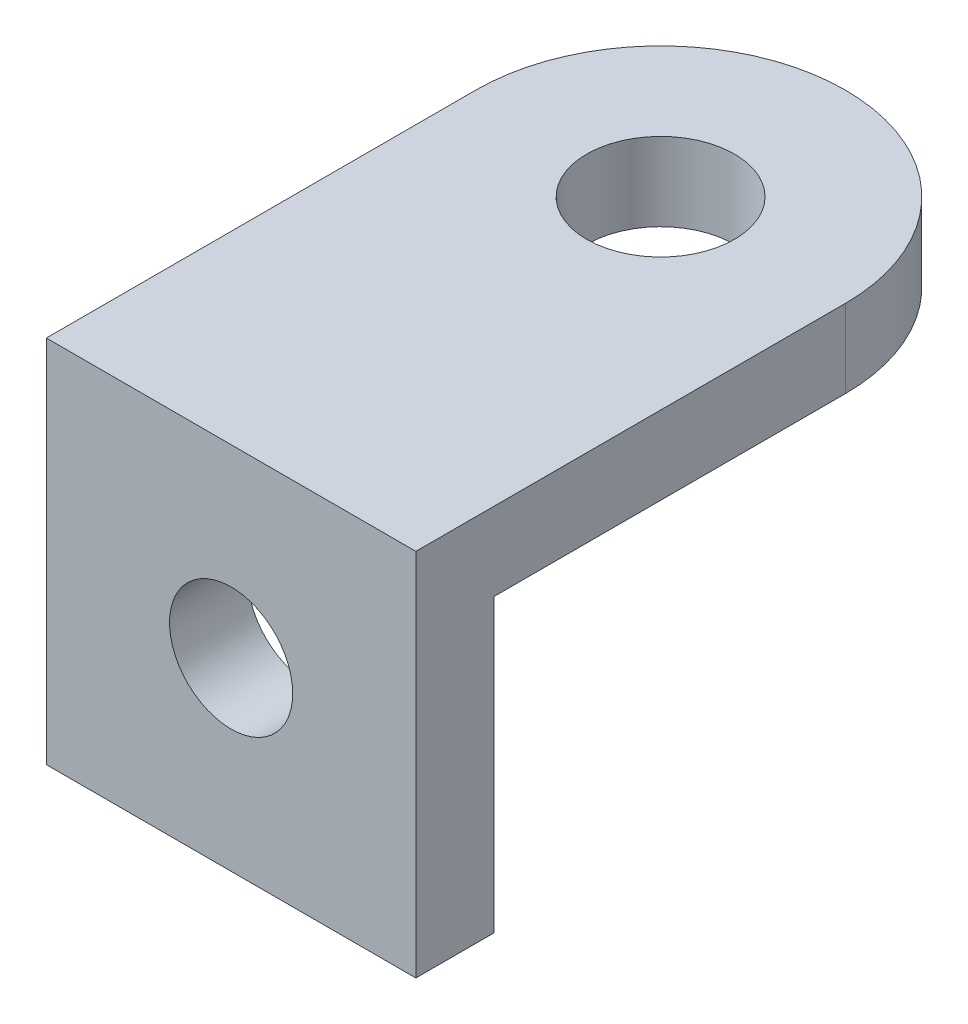
SolidWorks part; units mm, degrees
ref_plane "Front Plane" through (0, 0, 0) normal (0, 0, 1) x (1, 0, 0)
ref_plane "Top Plane" through (0, 0, 0) normal (0, 1, 0) x (1, 0, 0)
ref_plane "Right Plane" through (0, 0, 0) normal (1, 0, 0) x (0, 0, -1)
sketch "Sketch1" plane through (0, 0, 0) normal (0, 0, 1) x (1, 0, 0)
  line L1 (-7.5, 0) -> (7.5, 0)
  line L2 (-7.5, 0) -> (-7.5, -15)
  line L3 (-7.5, -15) -> (7.5, -15)
  line L4 (7.5, 0) -> (7.5, -15)
  line L5 (-7.5, 0) -> (7.5, -15) construction
  line L6 (-7.5, -15) -> (7.5, 0) construction
  circle A0 centre (0, -7.5) radius 2.5
  point P0 (0, -7.5)
  dimension "D3" = 5
  dimension "D1" = 15
  dimension "D2" = 15
extrude "Boss-Extrude1" add sketch "Sketch1" along normal blind 3.175
sketch "Sketch2" plane through (0, 0, 0) normal (0, 1, 0) x (1, 0, 0)
  line L6 (-7.5, 14.26) -> (-7.5, 0)
  line L7 (-7.5, 0) -> (7.5, 0)
  line L8 (7.5, 0) -> (7.5, 14.26)
  line L10 (0, 14.26) -> (0, 0) construction
  circle A0 centre (0, 14.26) radius 3
  arc A3 (7.5, 14.26) -> (-7.5, 14.26) centre (0, 14.26) ccw
  point P1 (-7.5, 0)
  dimension "D2" = 6
  dimension "D3" = 15
  dimension "D1" = 14.26
  dimension "D4" = 15
extrude "Boss-Extrude2" add sketch "Sketch2" against normal blind 3.175
